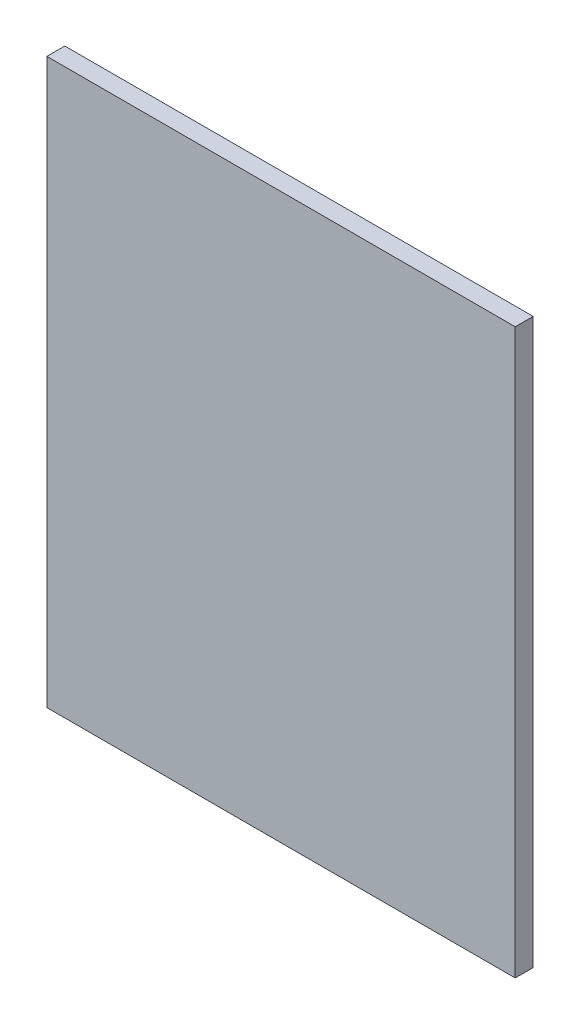
SolidWorks part; units mm, degrees
ref_plane "Front Plane" through (0, 0, 0) normal (0, 0, 1) x (1, 0, 0)
ref_plane "Top Plane" through (0, 0, 0) normal (0, 1, 0) x (1, 0, 0)
ref_plane "Right Plane" through (0, 0, 0) normal (1, 0, 0) x (0, 0, -1)
sketch "Sketch1" plane through (0, 0, 0) normal (0, 0, 1) x (1, 0, 0)
  line L1 (-235, -283) -> (235, -283)
  line L2 (-235, -283) -> (-235, 283)
  line L3 (-235, 283) -> (235, 283)
  line L4 (235, -283) -> (235, 283)
  line L5 (-235, -283) -> (235, 283) construction
  line L6 (-235, 283) -> (235, -283) construction
  point P0 (0, 0)
  dimension "D1" = 470
  dimension "D2" = 566
extrude "Boss-Extrude1" add sketch "Sketch1" along normal blind 18
equation "\"Case_Depth\" = 470mm"
equation "\"WoodSheet_Thickness\" = 18mm"
equation "\"D1@Sketch1\"=\"Case_Depth\""
equation "\"D1@Boss-Extrude1\"=\"WoodSheet_Thickness\""
equation "\"Case_Width\" = 790mm"
equation "\"Case_Height\" = 566mm"
equation "\"D2@Sketch1\"=\"Case_Height\""
